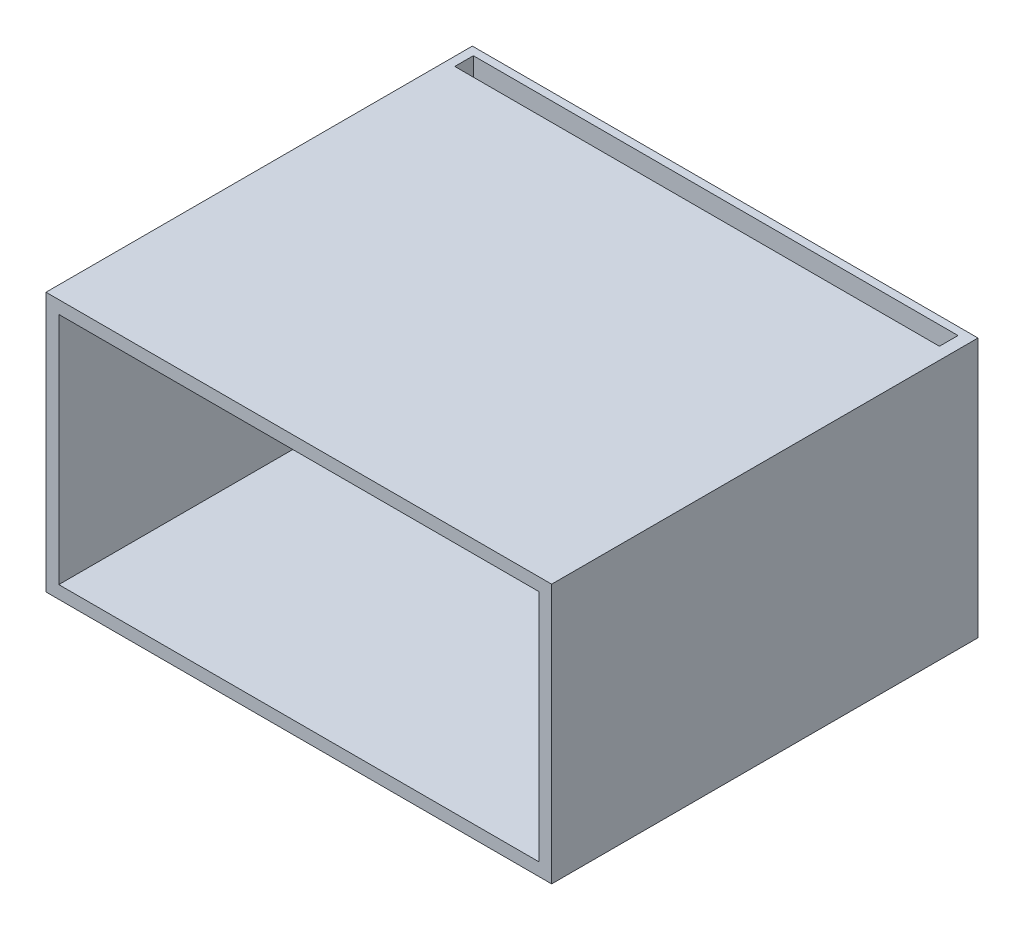
SolidWorks part; units mm, degrees
ref_plane "Front Plane" through (0, 0, 0) normal (0, 0, 1) x (1, 0, 0)
ref_plane "Top Plane" through (0, 0, 0) normal (0, 1, 0) x (1, 0, 0)
ref_plane "Right Plane" through (0, 0, 0) normal (1, 0, 0) x (0, 0, -1)
sketch "Sketch1" plane through (0, 0, 0) normal (0, 0, 1) x (1, 0, 0)
  line L1 (0, 0) -> (394.9267, 0)
  line L2 (0, 0) -> (0, 202.7697)
  line L3 (0, 202.7697) -> (394.9267, 202.7697)
  line L4 (394.9267, 0) -> (394.9267, 202.7697)
extrude "Boss-Extrude1" add sketch "Sketch1" along normal blind 333
shell "Shell5" thickness 10
ref_plane "Plane2" through (0, 0, 166.5) normal (0, 0, 1) x (1, 0, 0)
sketch "Sketch18" plane through (0, 0, 166.5) normal (0, 0, 1) x (1, 0, 0)
  line L0 (10, 128.3559) -> (81.8144, 128.3559)
  line L1 (10, 192.7697) -> (10, 10) construction
  line L2 (81.8144, 57.9602) -> (10, 57.9602)
  line L3 (10, 192.7697) -> (10, 10) construction
  line L4 (10, 57.9602) -> (10, 128.3559)
  arc A0 (81.8144, 128.3559) -> (81.8144, 57.9602) centre (81.8144, 93.1581) cw
extrude "Boss-Extrude2" add sketch "Sketch18" along normal mid plane 14
sketch "Sketch19" plane through (0, 0, 173.5) normal (0, 0, 1) x (1, 0, 0)
  circle A0 centre (81.8144, 93.1581) radius 24.923
  arc A1 (81.8144, 57.9602) -> (81.8144, 128.3559) centre (81.8144, 93.1581) ccw construction
extrude "Cut-Extrude1" cut sketch "Sketch19" against normal blind 14
sketch "Sketch22" plane through (0, 0, 166.5) normal (0, 0, 1) x (1, 0, 0)
  line L0 (384.9267, 128.3559) -> (291.109, 128.3559)
  line L1 (384.9267, 10) -> (384.9267, 192.7697) construction
  line L2 (291.109, 59.382) -> (384.9267, 59.382)
  line L3 (384.9267, 59.382) -> (384.9267, 128.3559)
  arc A0 (291.109, 128.3559) -> (291.109, 59.382) centre (291.109, 93.869) ccw
extrude "Boss-Extrude3" add sketch "Sketch22" along normal mid plane 14
sketch "Sketch23" plane through (0, 0, 173.5) normal (0, 0, 1) x (1, 0, 0)
  circle A0 centre (291.109, 93.869) radius 24.923
  circle A1 centre (81.8144, 93.1581) radius 24.923 construction
  arc A2 (291.109, 128.3559) -> (291.109, 59.382) centre (291.109, 93.869) ccw construction
extrude "Cut-Extrude2" cut sketch "Sketch23" against normal blind 14
sketch "Sketch24" plane through (0, 202.7697, 0) normal (0, 1, 0) x (1, 0, 0)
  line L2 (6.9001, -6.123) -> (385.4501, -6.123)
  line L3 (6.9001, -6.123) -> (6.9001, -20.6542)
  line L4 (6.9001, -20.6542) -> (385.4501, -20.6542)
  line L5 (385.4501, -6.123) -> (385.4501, -20.6542)
extrude "Cut-Extrude6" cut sketch "Sketch24" against normal blind 30
sketch "Sketch25" plane through (0, 10, 0) normal (0, 1, 0) x (1, 0, 0)
  line L1 (6.9001, -20.6542) -> (32.8949, -20.6542)
  line L2 (6.9001, -20.6542) -> (6.9001, -31.5401)
  line L3 (6.9001, -31.5401) -> (32.8949, -31.5401)
  line L4 (32.8949, -20.6542) -> (32.8949, -31.5401)
extrude "Boss-Extrude5" add sketch "Sketch25" along normal blind 14
sketch "Sketch27" plane through (0, 10, 0) normal (0, 1, 0) x (1, 0, 0)
  line L1 (385.4501, -20.6542) -> (355.9714, -20.6542)
  line L2 (385.4501, -20.6542) -> (385.4501, -34.795)
  line L3 (385.4501, -34.795) -> (355.9714, -34.795)
  line L4 (355.9714, -20.6542) -> (355.9714, -34.795)
extrude "Boss-Extrude7" add sketch "Sketch27" along normal blind 14
sketch "Sketch33" plane through (0, 192.7697, 0) normal (0, -1, 0) x (1, 0, 0)
  line L0 (197.4633, 10) -> (197.4633, 132.0715)
  line L1 (10, 10) -> (384.9267, 10) construction
extrude "Extrude-Thin2" add sketch "Sketch33" along normal up to next thin contours L0
sketch "Sketch34" plane through (197.4633, 0, 0) normal (-1, 0, 0) x (0, 0, 1)
  line L0 (132.0715, 58.1579) -> (39.5152, 10)
  line L1 (132.0715, 10) -> (132.0715, 192.7697) construction
  line L2 (132.0715, 10) -> (10, 10) construction
  line L3 (39.5152, 10) -> (132.0715, 10)
  line L4 (132.0715, 10) -> (132.0715, 58.1579)
extrude "Cut-Extrude8" cut sketch "Sketch34" against normal blind 49
sketch "Sketch35" plane through (0, 192.7697, 0) normal (0, 1, 0) x (1, 0, 0)
  line L1 (197.4633, -10) -> (207.4633, -10)
  line L2 (197.4633, -10) -> (197.4633, -20.6542)
  line L3 (197.4633, -20.6542) -> (207.4633, -20.6542)
  line L4 (207.4633, -10) -> (207.4633, -20.6542)
extrude "Cut-Extrude11" cut sketch "Sketch35" against normal up to surface (182.7697 mm away) up to face at (197.9558, 10, 62.5198)
